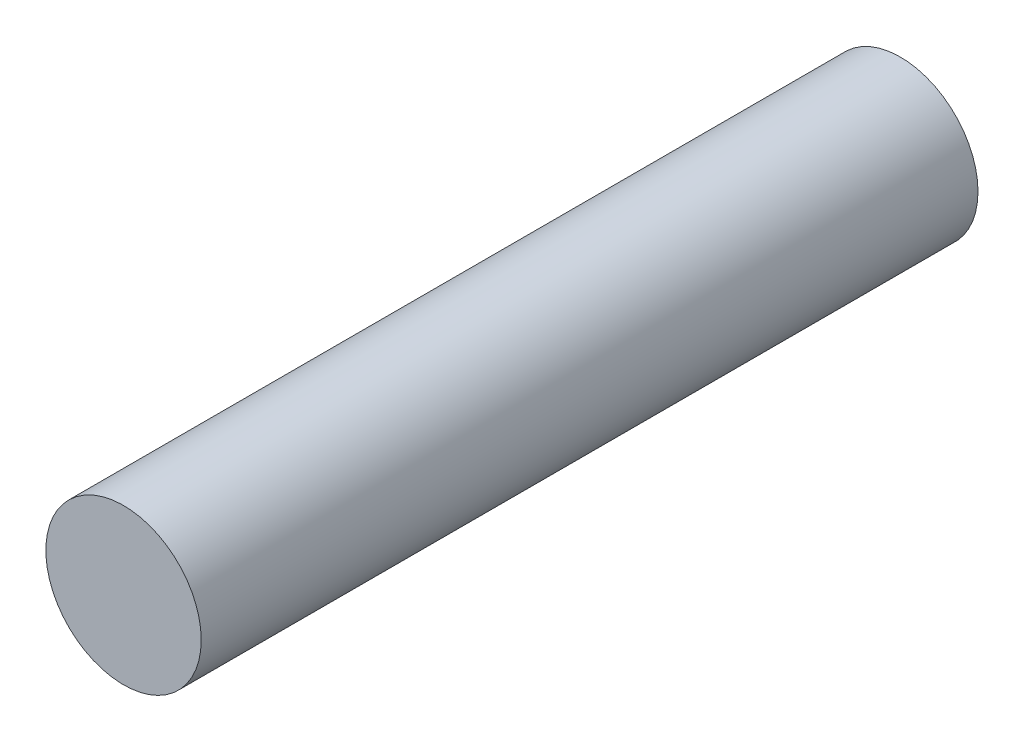
SolidWorks part; units mm, degrees
ref_plane "Plan de face" through (0, 0, 0) normal (0, 0, 1) x (1, 0, 0)
ref_plane "Plan de dessus" through (0, 0, 0) normal (0, 1, 0) x (1, 0, 0)
ref_plane "Plan de droite" through (0, 0, 0) normal (1, 0, 0) x (0, 0, -1)
sketch "Esquisse1" plane through (0, 0, 0) normal (0, 0, 1) x (1, 0, 0)
  circle A0 centre (0, 0) radius 15
  dimension "D1" = 30
extrude "Boss.-Extru.1" add sketch "Esquisse1" along normal blind 150
